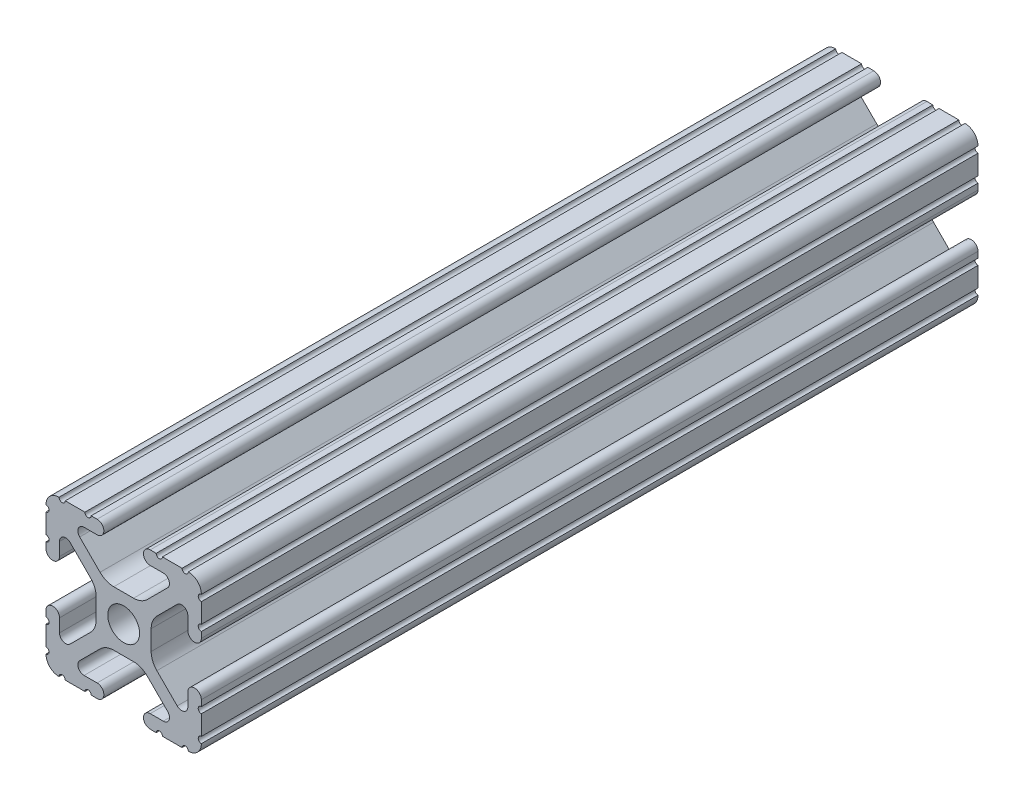
SolidWorks part; units mm, degrees
ref_plane "Front Plane" through (0, 0, 0) normal (0, 0, 1) x (1, 0, 0)
ref_plane "Top Plane" through (0, 0, 0) normal (0, 1, 0) x (1, 0, 0)
ref_plane "Right Plane" through (0, 0, 0) normal (1, 0, 0) x (0, 0, -1)
ref_plane "Plane1" through (0, 0, -25.4) normal (0, 0, -1) x (-1, 0, 0)
sketch "Sketch1" plane through (0, 0, -25.4) normal (0, 0, -1) x (-1, 0, 0)
  line L0 (12.7, -9.5504) -> (12.7, -6.3331)
  line L1 (12.7, -5.3171) -> (12.7, -4.3434)
  line L2 (10.4902, -4.3434) -> (10.4902, -6.4748)
  line L3 (8.7558, -7.1932) -> (5.4257, -3.8632)
  line L4 (4.4958, -1.6181) -> (4.4958, 1.6181)
  line L5 (5.4257, 3.8632) -> (8.7558, 7.1932)
  line L6 (10.4902, 6.4748) -> (10.4902, 4.3434)
  line L7 (12.7, 4.3434) -> (12.7, 5.3171)
  line L8 (12.7, 6.3331) -> (12.7, 9.5504)
  line L9 (9.5504, 12.7) -> (6.3331, 12.7)
  line L10 (5.3171, 12.7) -> (4.3434, 12.7)
  line L11 (4.3434, 10.4902) -> (6.4748, 10.4902)
  line L12 (7.1932, 8.7558) -> (3.8632, 5.4257)
  line L13 (1.6181, 4.4958) -> (-1.6181, 4.4958)
  line L14 (-3.8632, 5.4257) -> (-7.1932, 8.7558)
  line L15 (-6.4748, 10.4902) -> (-4.3434, 10.4902)
  line L16 (-4.3434, 12.7) -> (-5.3171, 12.7)
  line L17 (-6.3331, 12.7) -> (-9.5504, 12.7)
  line L18 (-12.7, 9.5504) -> (-12.7, 6.3331)
  line L19 (-12.7, 5.3171) -> (-12.7, 4.3434)
  line L20 (-10.4902, 4.3434) -> (-10.4902, 6.4748)
  line L21 (-8.7558, 7.1932) -> (-5.4257, 3.8632)
  line L22 (-4.4958, 1.6181) -> (-4.4958, -1.6181)
  line L23 (-5.4257, -3.8632) -> (-8.7558, -7.1932)
  line L24 (-10.4902, -6.4748) -> (-10.4902, -4.3434)
  line L25 (-12.7, -4.3434) -> (-12.7, -5.3171)
  line L26 (-12.7, -6.3331) -> (-12.7, -9.5504)
  line L27 (-9.5504, -12.7) -> (-6.3331, -12.7)
  line L28 (-5.3171, -12.7) -> (-4.3434, -12.7)
  line L29 (-4.3434, -10.4902) -> (-6.4748, -10.4902)
  line L30 (-7.1932, -8.7558) -> (-3.8632, -5.4257)
  line L31 (-1.6181, -4.4958) -> (1.6181, -4.4958)
  line L32 (3.8632, -5.4257) -> (7.1932, -8.7558)
  line L33 (6.4748, -10.4902) -> (4.3434, -10.4902)
  line L34 (4.3434, -12.7) -> (5.3171, -12.7)
  line L35 (6.3331, -12.7) -> (9.5504, -12.7)
  arc A0 (12.6998, -10.5664) -> (12.7, -9.5504) centre (12.7, -10.0584) cw
  arc A1 (12.7, -6.3331) -> (12.7, -5.3171) centre (12.7, -5.8251) cw
  arc A2 (12.7, -4.3434) -> (10.4902, -4.3434) centre (11.5951, -4.3434) ccw
  arc A3 (10.4902, -6.4748) -> (8.7558, -7.1932) centre (9.4742, -6.4748) cw
  arc A4 (5.4257, -3.8632) -> (4.4958, -1.6181) centre (7.6708, -1.6181) cw
  arc A5 (4.4958, 1.6181) -> (5.4257, 3.8632) centre (7.6708, 1.6181) cw
  arc A6 (8.7558, 7.1932) -> (10.4902, 6.4748) centre (9.4742, 6.4748) cw
  arc A7 (10.4902, 4.3434) -> (12.7, 4.3434) centre (11.5951, 4.3434) ccw
  arc A8 (12.7, 5.3171) -> (12.7, 6.3331) centre (12.7, 5.8251) cw
  arc A9 (12.7, 9.5504) -> (12.6998, 10.5664) centre (12.7, 10.0584) cw
  arc A10 (12.6998, 10.5664) -> (10.5664, 12.6998) centre (10.5918, 10.5918) ccw
  arc A11 (10.5664, 12.6998) -> (9.5504, 12.7) centre (10.0584, 12.7) cw
  arc A12 (6.3331, 12.7) -> (5.3171, 12.7) centre (5.8251, 12.7) cw
  arc A13 (4.3434, 12.7) -> (4.3434, 10.4902) centre (4.3434, 11.5951) ccw
  arc A14 (6.4748, 10.4902) -> (7.1932, 8.7558) centre (6.4748, 9.4742) cw
  arc A15 (3.8632, 5.4257) -> (1.6181, 4.4958) centre (1.6181, 7.6708) cw
  arc A16 (-1.6181, 4.4958) -> (-3.8632, 5.4257) centre (-1.6181, 7.6708) cw
  arc A17 (-7.1932, 8.7558) -> (-6.4748, 10.4902) centre (-6.4748, 9.4742) cw
  arc A18 (-4.3434, 10.4902) -> (-4.3434, 12.7) centre (-4.3434, 11.5951) ccw
  arc A19 (-5.3171, 12.7) -> (-6.3331, 12.7) centre (-5.8251, 12.7) cw
  arc A20 (-9.5504, 12.7) -> (-10.5664, 12.6998) centre (-10.0584, 12.7) cw
  arc A21 (-10.5664, 12.6998) -> (-12.6998, 10.5664) centre (-10.5918, 10.5918) ccw
  arc A22 (-12.6998, 10.5664) -> (-12.7, 9.5504) centre (-12.7, 10.0584) cw
  arc A23 (-12.7, 6.3331) -> (-12.7, 5.3171) centre (-12.7, 5.8251) cw
  arc A24 (-12.7, 4.3434) -> (-10.4902, 4.3434) centre (-11.5951, 4.3434) ccw
  arc A25 (-10.4902, 6.4748) -> (-8.7558, 7.1932) centre (-9.4742, 6.4748) cw
  arc A26 (-5.4257, 3.8632) -> (-4.4958, 1.6181) centre (-7.6708, 1.6181) cw
  arc A27 (-4.4958, -1.6181) -> (-5.4257, -3.8632) centre (-7.6708, -1.6181) cw
  arc A28 (-8.7558, -7.1932) -> (-10.4902, -6.4748) centre (-9.4742, -6.4748) cw
  arc A29 (-10.4902, -4.3434) -> (-12.7, -4.3434) centre (-11.5951, -4.3434) ccw
  arc A30 (-12.7, -5.3171) -> (-12.7, -6.3331) centre (-12.7, -5.8251) cw
  arc A31 (-12.7, -9.5504) -> (-12.6998, -10.5664) centre (-12.7, -10.0584) cw
  arc A32 (-12.6998, -10.5664) -> (-10.5664, -12.6998) centre (-10.5918, -10.5918) ccw
  arc A33 (-10.5664, -12.6998) -> (-9.5504, -12.7) centre (-10.0584, -12.7) cw
  arc A34 (-6.3331, -12.7) -> (-5.3171, -12.7) centre (-5.8251, -12.7) cw
  arc A35 (-4.3434, -12.7) -> (-4.3434, -10.4902) centre (-4.3434, -11.5951) ccw
  arc A36 (-6.4748, -10.4902) -> (-7.1932, -8.7558) centre (-6.4748, -9.4742) cw
  arc A37 (-3.8632, -5.4257) -> (-1.6181, -4.4958) centre (-1.6181, -7.6708) cw
  arc A38 (1.6181, -4.4958) -> (3.8632, -5.4257) centre (1.6181, -7.6708) cw
  arc A39 (7.1932, -8.7558) -> (6.4748, -10.4902) centre (6.4748, -9.4742) cw
  arc A40 (4.3434, -10.4902) -> (4.3434, -12.7) centre (4.3434, -11.5951) ccw
  arc A41 (5.3171, -12.7) -> (6.3331, -12.7) centre (5.8251, -12.7) cw
  arc A42 (9.5504, -12.7) -> (10.5664, -12.6998) centre (10.0584, -12.7) cw
  arc A43 (10.5664, -12.6998) -> (12.6998, -10.5664) centre (10.5918, -10.5918) ccw
  circle A44 centre (0, 0) radius 2.6035
extrude "Boss-Extrude1" add sketch "Sketch1" against normal blind 127
